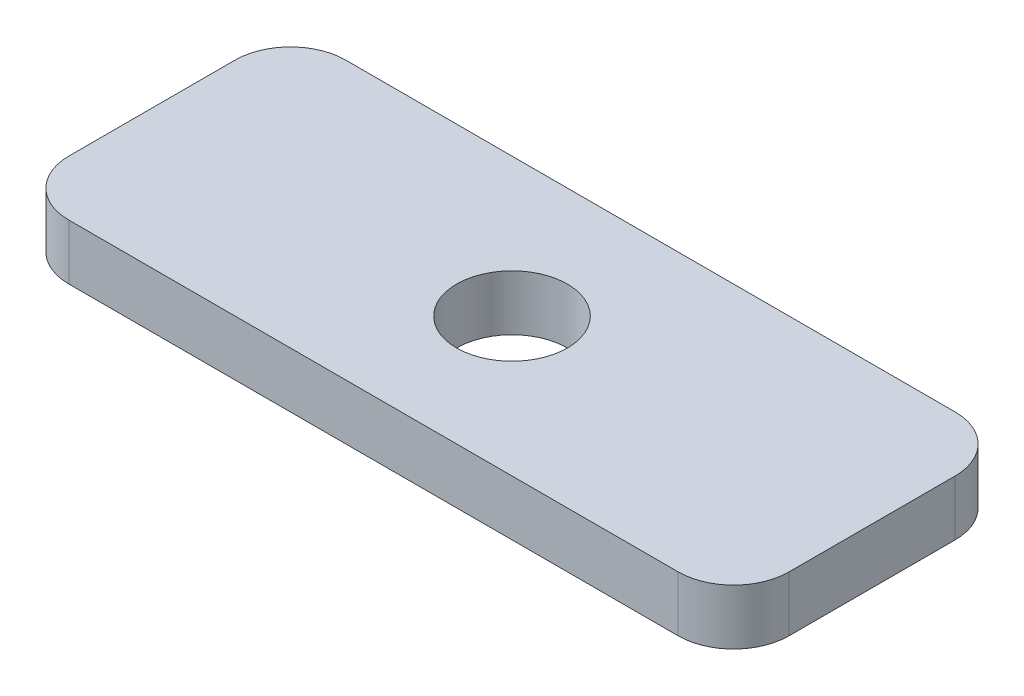
SolidWorks part; units mm, degrees
ref_plane "Front Plane" through (0, 0, 0) normal (0, 0, 1) x (1, 0, 0)
ref_plane "Top Plane" through (0, 0, 0) normal (0, 1, 0) x (1, 0, 0)
ref_plane "Right Plane" through (0, 0, 0) normal (1, 0, 0) x (0, 0, -1)
sketch "Sketch1" plane through (0, 0, 0) normal (0, 1, 0) x (1, 0, 0)
  line L0 (0, 10) -> (26, 0) construction
  line L1 (0, 0) -> (26, 0)
  line L2 (0, 0) -> (0, 10)
  line L3 (0, 10) -> (26, 10)
  line L4 (26, 0) -> (26, 10)
  circle A0 centre (13, 5) radius 2
  dimension "D3" = 4
  dimension "D1" = 10
  dimension "D2" = 26
extrude "Boss-Extrude1" add sketch "Sketch1" along normal blind 2
fillet "Fillet1" radius 2 4 edges at (0, 1, -10) (26, 1, -10) (0, 1, 0) (26, 1, 0)
